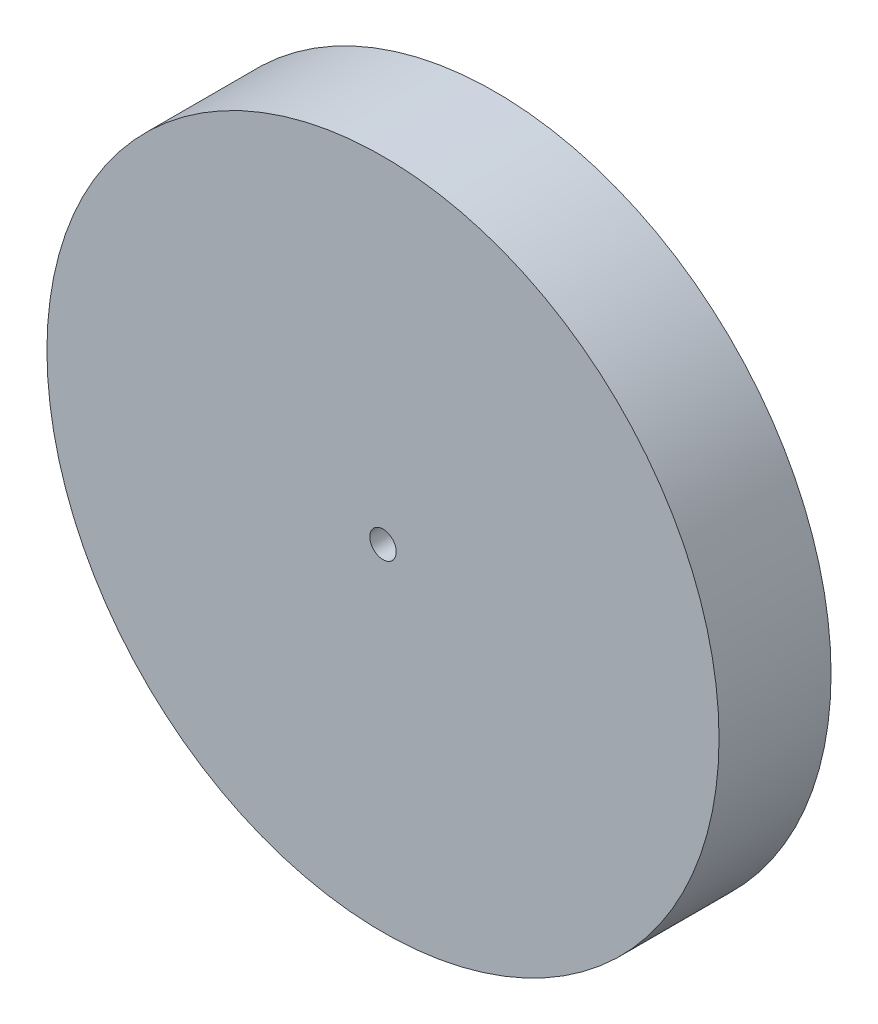
SolidWorks part; units mm, degrees
ref_plane "Front Plane" through (0, 0, 0) normal (0, 0, 1) x (1, 0, 0)
ref_plane "Top Plane" through (0, 0, 0) normal (0, 1, 0) x (1, 0, 0)
ref_plane "Right Plane" through (0, 0, 0) normal (1, 0, 0) x (0, 0, -1)
sketch "Sketch1" plane through (0, 0, 0) normal (0, 0, 1) x (1, 0, 0)
  circle A0 centre (0, 0) radius 76.2
  circle A1 centre (0, 0) radius 3
  dimension "D1" = 152.4
  dimension "D2" = 6
extrude "Boss-Extrude1" add sketch "Sketch1" along normal blind 25.4
